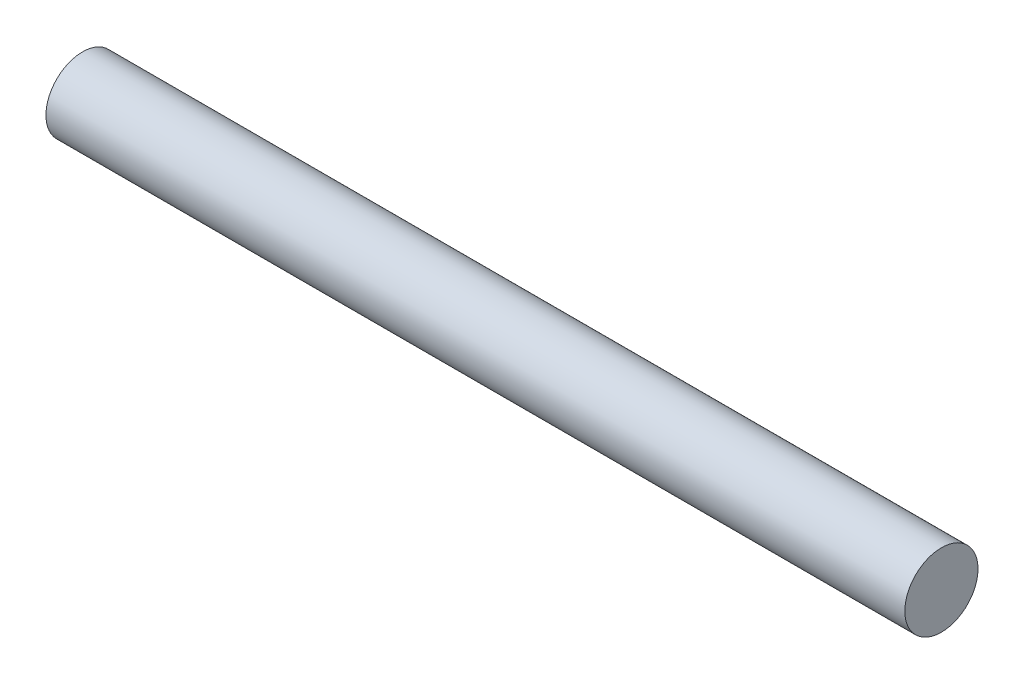
SolidWorks part; units mm, degrees
material "Brass"
ref_plane "Front Plane" through (0, 0, 0) normal (0, 0, 1) x (1, 0, 0)
ref_plane "Top Plane" through (0, 0, 0) normal (0, 1, 0) x (1, 0, 0)
ref_plane "Right Plane" through (0, 0, 0) normal (1, 0, 0) x (0, 0, -1)
sketch "Sketch1" plane through (0, 0, 0) normal (1, 0, 0) x (0, 0, -1)
  circle A0 centre (0, 0) radius 2.5
  dimension "D1" = 5
extrude "Boss-Extrude1" add sketch "Sketch1" along normal blind 58.674
